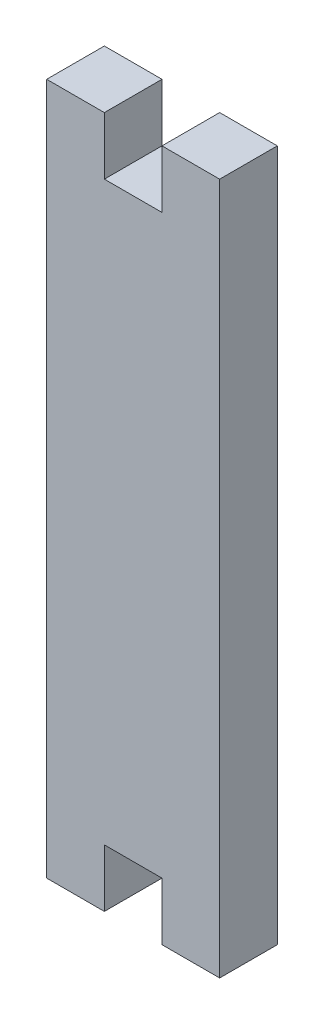
SolidWorks part; units mm, degrees
ref_plane "Front Plane" through (0, 0, 0) normal (0, 0, 1) x (1, 0, 0)
ref_plane "Top Plane" through (0, 0, 0) normal (0, 1, 0) x (1, 0, 0)
ref_plane "Right Plane" through (0, 0, 0) normal (1, 0, 0) x (0, 0, -1)
sketch "Sketch1" plane through (0, 0, 0) normal (0, 0, 1) x (1, 0, 0)
  line L0 (0.9889, -0.2737) -> (9.9889, -0.2737) construction
  line L5 (0.9889, 17.7263) -> (3.9889, 17.7263)
  line L6 (0.9889, 17.7263) -> (0.9889, -18.2737)
  line L15 (0.9889, -18.2737) -> (3.9889, -18.2737)
  line L16 (9.9889, 17.7263) -> (9.9889, -18.2737)
  line L17 (3.9889, -15.2737) -> (6.9889, -15.2737)
  line L18 (3.9889, -15.2737) -> (3.9889, -18.2737)
  line L20 (6.9889, -15.2737) -> (6.9889, -18.2737)
  line L22 (6.9889, 14.7263) -> (6.9889, 17.7263)
  line L23 (3.9889, 14.7263) -> (6.9889, 14.7263)
  line L24 (3.9889, 14.7263) -> (3.9889, 17.7263)
  line L25 (6.9889, 17.7263) -> (9.9889, 17.7263)
  line L26 (6.9889, -18.2737) -> (9.9889, -18.2737)
  dimension "D1" = 36
  dimension "D2" = 9
  dimension "D3" = 3
  dimension "D4" = 3
  dimension "D5" = 30
  dimension "D6" = 3
extrude "Boss-Extrude2" add sketch "Sketch1" along normal blind 3
